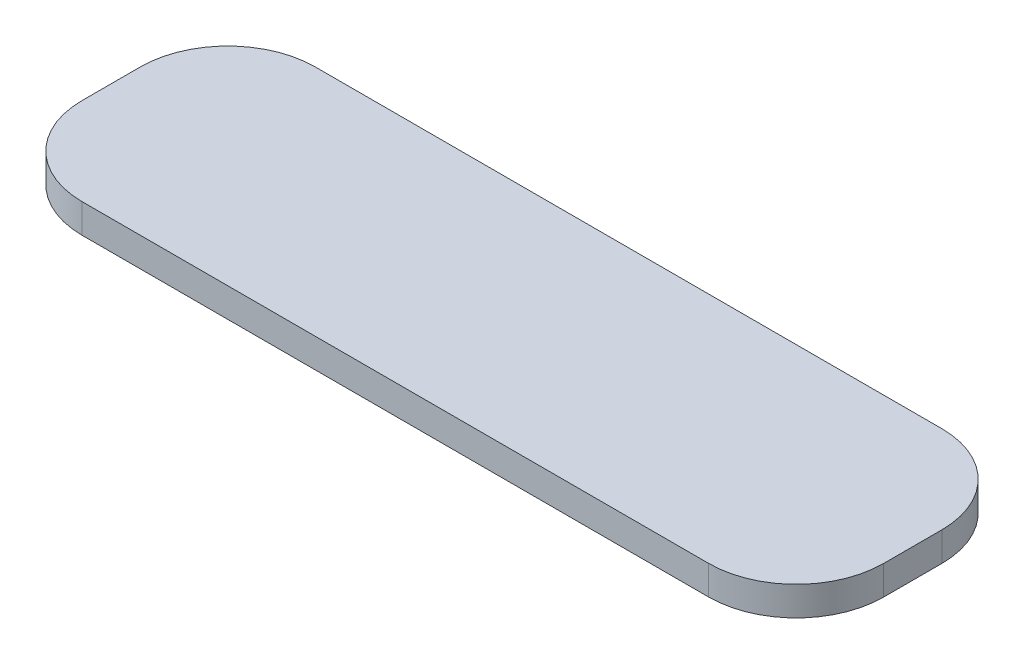
SolidWorks part; units mm, degrees
ref_plane "Спереди" through (0, 0, 0) normal (0, 0, 1) x (1, 0, 0)
ref_plane "Сверху" through (0, 0, 0) normal (0, 1, 0) x (1, 0, 0)
ref_plane "Справа" through (0, 0, 0) normal (1, 0, 0) x (0, 0, -1)
sketch "Эскиз1" plane through (0, 0, 0) normal (0, 1, 0) x (1, 0, 0)
  line L1 (-33.8905, -65.4788) -> (181.1095, -65.4788)
  line L2 (-63.8905, -35.4788) -> (-63.8905, -15.4587)
  line L3 (-33.8905, 14.5413) -> (181.1095, 14.5413)
  line L4 (211.1095, -35.4788) -> (211.1095, -15.4587)
  arc A0 (181.1095, 14.5413) -> (211.1095, -15.4587) centre (181.1095, -15.4587) cw
  arc A1 (181.1095, -65.4788) -> (211.1095, -35.4788) centre (181.1095, -35.4788) ccw
  arc A2 (-33.8905, -65.4788) -> (-63.8905, -35.4788) centre (-33.8905, -35.4788) cw
  arc A3 (-63.8905, -15.4587) -> (-33.8905, 14.5413) centre (-33.8905, -15.4587) cw
extrude "Бобышка-Вытянуть1" add sketch "Эскиз1" along normal blind 10
